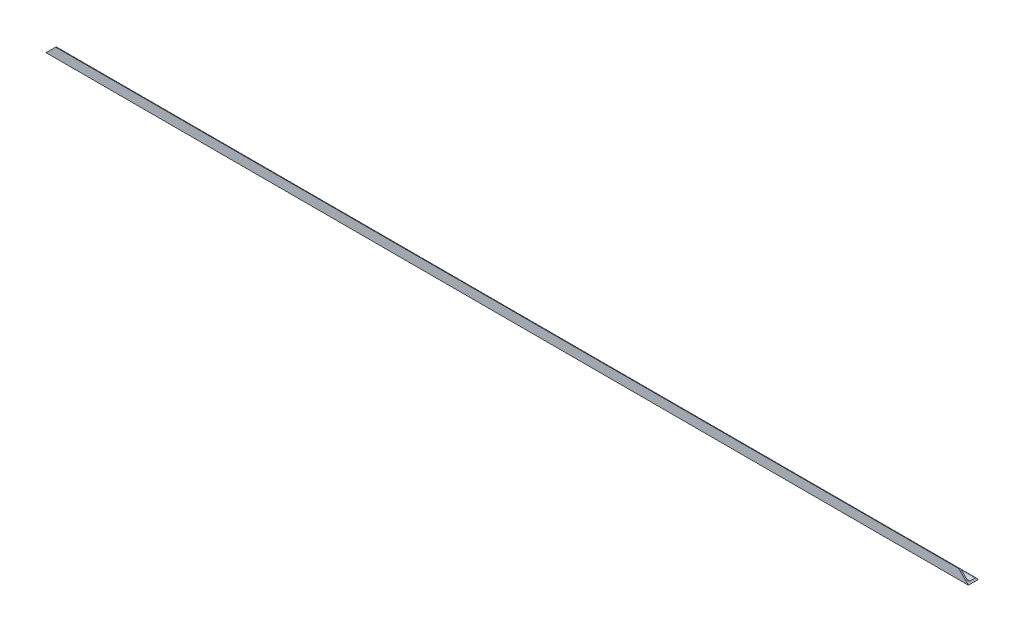
SolidWorks part; units mm, degrees
ref_plane "Front Plane" through (0, 0, 0) normal (0, 0, 1) x (1, 0, 0)
ref_plane "Top Plane" through (0, 0, 0) normal (0, 1, 0) x (1, 0, 0)
ref_plane "Right Plane" through (0, 0, 0) normal (1, 0, 0) x (0, 0, -1)
sketch "Sketch1" plane through (0, 0, 0) normal (0, 1, 0) x (1, 0, 0)
  line L0 (0, 0) -> (1920, 0)
  dimension "D1" = 1920
other "L angle (equal) 20X20X3(2)"
ref_plane "Plane1" through (0, 0, 0) normal (1, 0, 0) x (0, 0, -1)
sketch "Sketch16" plane through (0, 0, 0) normal (1, 0, 0) x (0, 0, -1)
  line L0 (0, 20) -> (0, 0)
  line L2 (3, 17) -> (3, 6.5)
  line L3 (6.5, 3) -> (17, 3)
  line L5 (20, 0) -> (0, 0)
  arc A0 (3, 17) -> (0, 20) centre (0, 17) ccw
  arc A1 (20, 0) -> (17, 3) centre (17, 0) ccw
  arc A2 (6.5, 3) -> (3, 6.5) centre (6.5, 6.5) cw
  point P8 (0, 10)
  point P9 (10, 0)
  point P10 (0, 0)
  dimension "Radius_2" = 3
  dimension "Radius_1" = 3.5
  dimension "V_leg" = 20
  dimension "H_leg" = 20
  dimension "thickness" = 3
sketch "Sketch14" plane through (0, 0, 0) normal (0, 0, 1) x (1, 0, 0)
  line L0 (1920, 0) -> (1920, 20)
  line L1 (0, 20) -> (0, 0)
  line L2 (20, 20) -> (0, 0)
  line L3 (1900, 20) -> (1920, 0)
  line L4 (0, 20) -> (0, 0)
  line L5 (0, 0) -> (1920, 0)
  line L6 (1920, 0) -> (1920, 20)
  line L7 (1920, 20) -> (0, 20)
  line L8 (0, 20) -> (0, 0) construction
  line L10 (1920, 0) -> (1920, 20) construction
  line L11 (1920, 20) -> (1900, 20)
  line L12 (20, 20) -> (0, 20)
  dimension "D2" = 20
  dimension "D3" = 20
  dimension "D1" = 0
extrude "Cut-Extrude1" cut sketch "Sketch14" against normal through all
